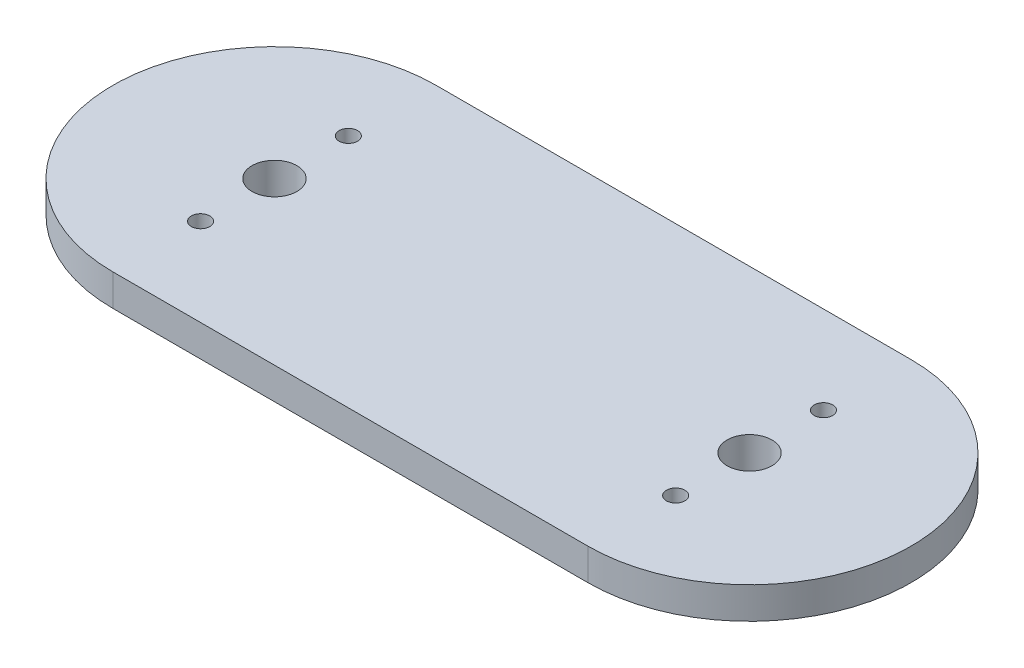
SolidWorks part; units mm, degrees
ref_plane "Front Plane" through (0, 0, 0) normal (0, 0, 1) x (1, 0, 0)
ref_plane "Top Plane" through (0, 0, 0) normal (0, 1, 0) x (1, 0, 0)
ref_plane "Right Plane" through (0, 0, 0) normal (1, 0, 0) x (0, 0, -1)
sketch "Sketch1" plane through (0, 0, 0) normal (0, 1, 0) x (1, 0, 0)
  line L0 (-31.9723, 0) -> (13.0277, 0)
  line L1 (13.0277, -30.6106) -> (-31.9723, -30.6106)
  arc A0 (13.0277, 0) -> (13.0277, -30.6106) centre (13.0277, -15.3053) cw
  arc A1 (-31.9723, -30.6106) -> (-31.9723, 0) centre (-31.9723, -15.3053) cw
  dimension "D1" = 45
  dimension "D2" = 30.6106
extrude "Boss-Extrude1" add sketch "Sketch1" along normal blind 3
sketch "Sketch2" plane through (0, 3, 0) normal (0, 1, 0) x (1, 0, 0)
  line L0 (-9.4723, -54.7734) -> (-9.4723, 0) construction
  line L1 (-31.9723, 0) -> (-31.9723, -30.6106) construction
  line L2 (-54.6054, -15.3053) -> (-9.4723, -15.3053) construction
  line L3 (13.0277, 0) -> (-31.9723, 0) construction
  circle A0 centre (-31.9723, -15.3053) radius 2.125
  circle A1 centre (-31.9723, -8.3053) radius 0.875
  circle A2 centre (-31.9723, -22.3053) radius 0.875
  circle A3 centre (13.0277, -8.3053) radius 0.875
  circle A4 centre (13.0277, -15.3053) radius 2.125
  circle A5 centre (13.0277, -22.3053) radius 0.875
  point P23 (-9.4723, 0)
  dimension "D1" = 4.25
  dimension "D2" = 1.75
  dimension "D3" = 7
extrude "Cut-Extrude1" cut sketch "Sketch2" against normal through all
